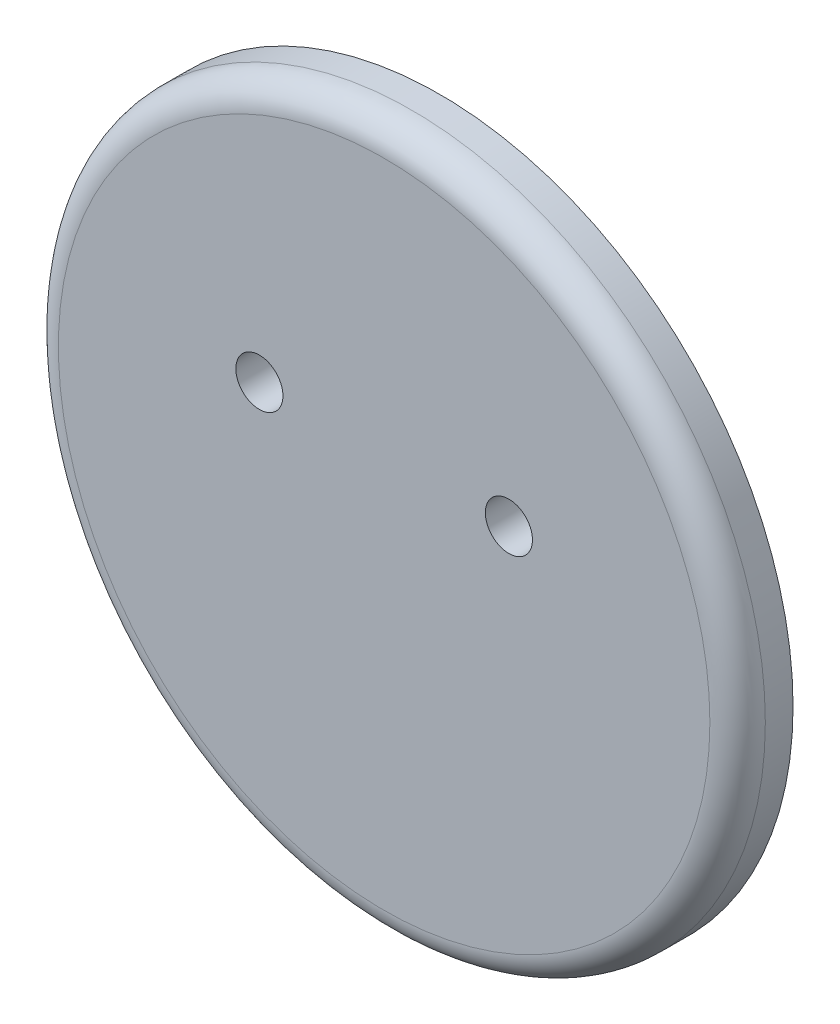
SolidWorks part; units mm, degrees
ref_plane "Front Plane" through (0, 0, 0) normal (0, 0, 1) x (1, 0, 0)
ref_plane "Top Plane" through (0, 0, 0) normal (0, 1, 0) x (1, 0, 0)
ref_plane "Right Plane" through (0, 0, 0) normal (1, 0, 0) x (0, 0, -1)
sketch "Sketch1" plane through (0, 0, 0) normal (0, 0, 1) x (1, 0, 0)
  circle A0 centre (0, 0) radius 25.5
  dimension "D1" = 51
extrude "Boss-Extrude1" add sketch "Sketch1" along normal blind 4
sketch "Sketch3" plane through (0, 0, 0) normal (0, 0, -1) x (-1, 0, 0)
  circle A0 centre (0, 0) radius 24.5
  circle A1 centre (0, 0) radius 18.5
  dimension "D1" = 49
  dimension "D2" = 37
extrude "Cut-Extrude1" cut sketch "Sketch3" against normal blind 1.675
fillet "Fillet1" radius 1.5 2 edges at (-18.5, 0, 1.675) (-24.5, 0, 1.675)
fillet "Fillet2" radius 2 1 edges at (25.5, 0, 4)
sketch "Sketch4" plane through (0, 0, 0) normal (0, 0, -1) x (-1, 0, 0)
  line L0 (0, 42.6162) -> (0, -52.674) construction
  line L1 (-53.5532, 0) -> (64.1911, 0) construction
  circle A0 centre (-9, 5) radius 1.7
  circle A1 centre (9, 5) radius 1.7
  dimension "D1" = 3.4
  dimension "D2" = 3.4
  dimension "D3" = 5
  dimension "D4" = 5
  dimension "D5" = 9
  dimension "D6" = 9
extrude "Cut-Extrude2" cut sketch "Sketch4" against normal blind 4
sketch "Sketch5" plane through (0, 0, 0) normal (0, 0, -1) x (-1, 0, 0)
  line L0 (0, 37.7656) -> (0, -39.4767) construction
  line L1 (-45.3133, 0) -> (45.8319, 0) construction
